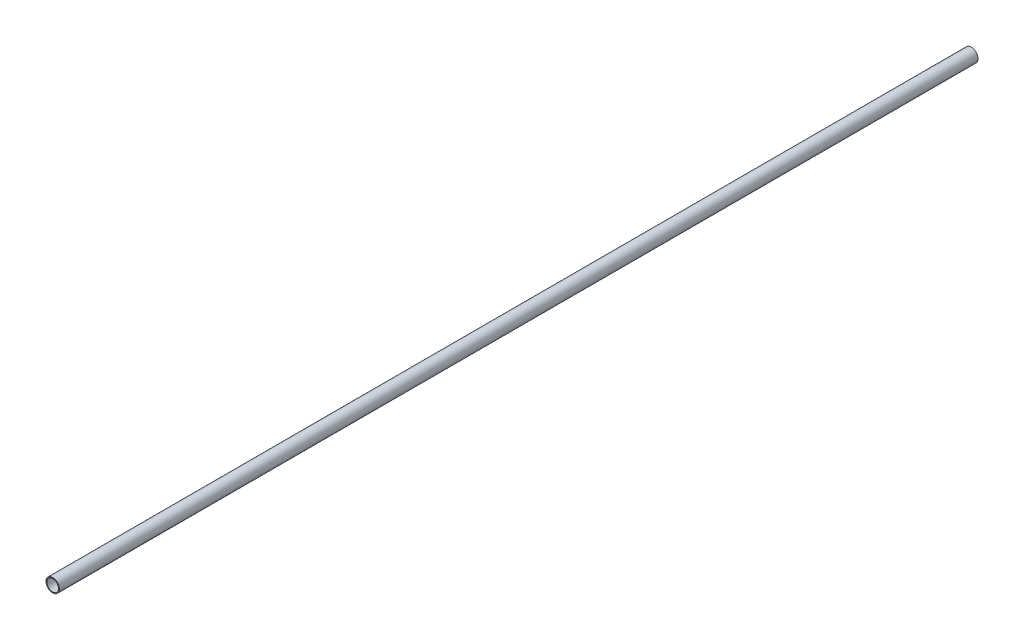
SolidWorks part; units mm, degrees
material "carbon fiber"
ref_plane "Front Plane" through (0, 0, 0) normal (0, 0, 1) x (1, 0, 0)
ref_plane "Top Plane" through (0, 0, 0) normal (0, 1, 0) x (1, 0, 0)
ref_plane "Right Plane" through (0, 0, 0) normal (1, 0, 0) x (0, 0, -1)
sketch "Эскиз1" plane through (0, 0, 0) normal (0, 0, 1) x (1, 0, 0)
  circle A0 centre (0, 0) radius 7
  circle A1 centre (0, 0) radius 8
  dimension "D1" = 1
  dimension "D2" = 14
extrude "Бобышка-Вытянуть1" add sketch "Эскиз1" along normal mid plane 1100
